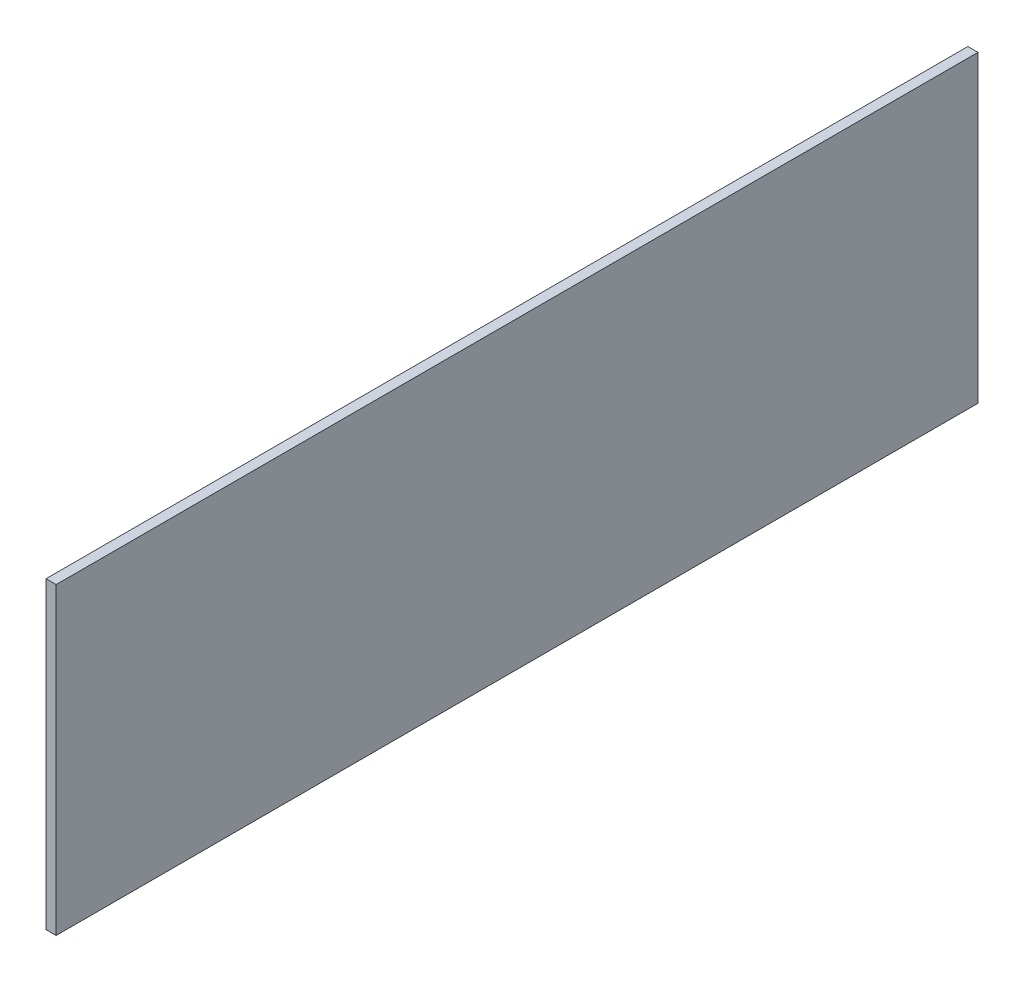
SolidWorks part; units mm, degrees
ref_plane "Front Plane" through (0, 0, 0) normal (0, 0, 1) x (1, 0, 0)
ref_plane "Top Plane" through (0, 0, 0) normal (0, 1, 0) x (1, 0, 0)
ref_plane "Right Plane" through (0, 0, 0) normal (1, 0, 0) x (0, 0, -1)
sketch "Sketch1" plane through (60, 0, 0) normal (1, 0, 0) x (0, 0, -1)
  line L1 (92, 60) -> (-90, 60)
  line L2 (92, 60) -> (92, 0)
  line L3 (92, 0) -> (-90, 0)
  line L4 (-90, 60) -> (-90, 0)
  line L5 (92, 0) -> (92, 60) construction
extrude "Boss-Extrude1" add sketch "Sketch1" along normal blind 2 contours L1 L4 L3 L2
